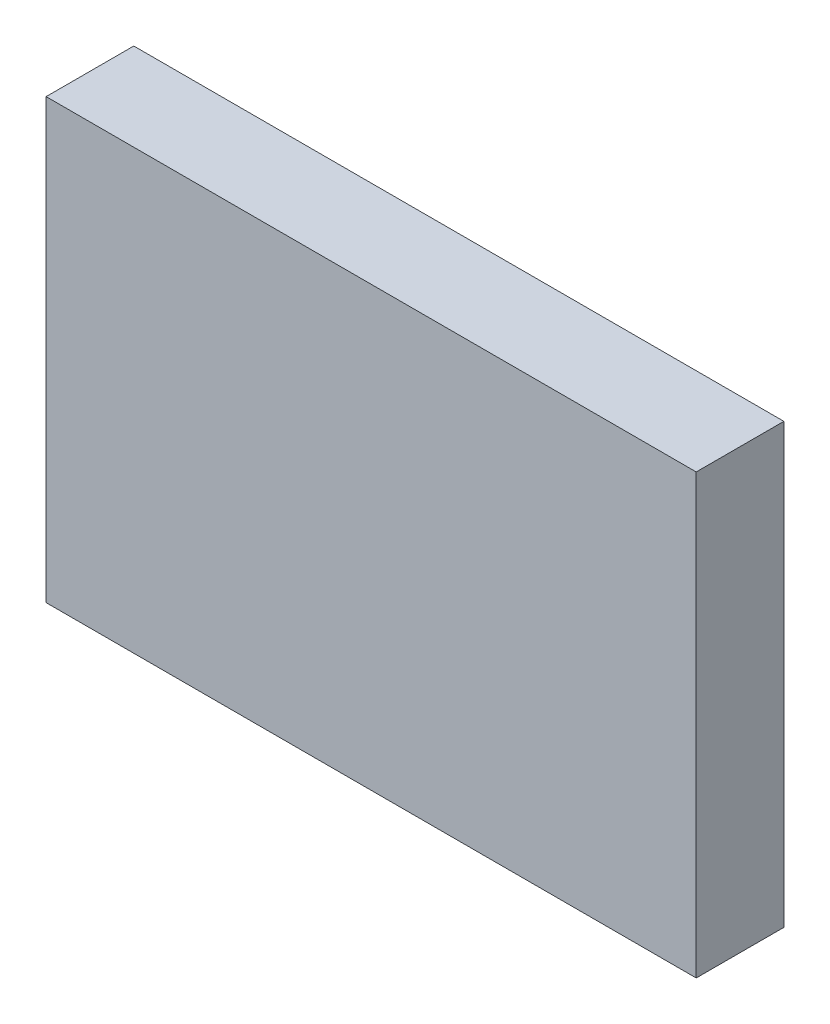
SolidWorks part; units mm, degrees
ref_plane "Front Plane" through (0, 0, 0) normal (0, 0, 1) x (1, 0, 0)
ref_plane "Top Plane" through (0, 0, 0) normal (0, 1, 0) x (1, 0, 0)
ref_plane "Right Plane" through (0, 0, 0) normal (1, 0, 0) x (0, 0, -1)
sketch "Sketch1" plane through (0, 0, 0) normal (0, 0, 1) x (1, 0, 0)
  line L1 (-222.5, 150) -> (222.5, 150)
  line L2 (-222.5, 150) -> (-222.5, -150)
  line L3 (-222.5, -150) -> (222.5, -150)
  line L4 (222.5, 150) -> (222.5, -150)
  line L5 (-222.5, 150) -> (222.5, -150) construction
  line L6 (-222.5, -150) -> (222.5, 150) construction
  point P0 (0, 0)
  dimension "D1" = 445
  dimension "D2" = 300
extrude "Boss-Extrude1" add sketch "Sketch1" along normal mid plane 60
